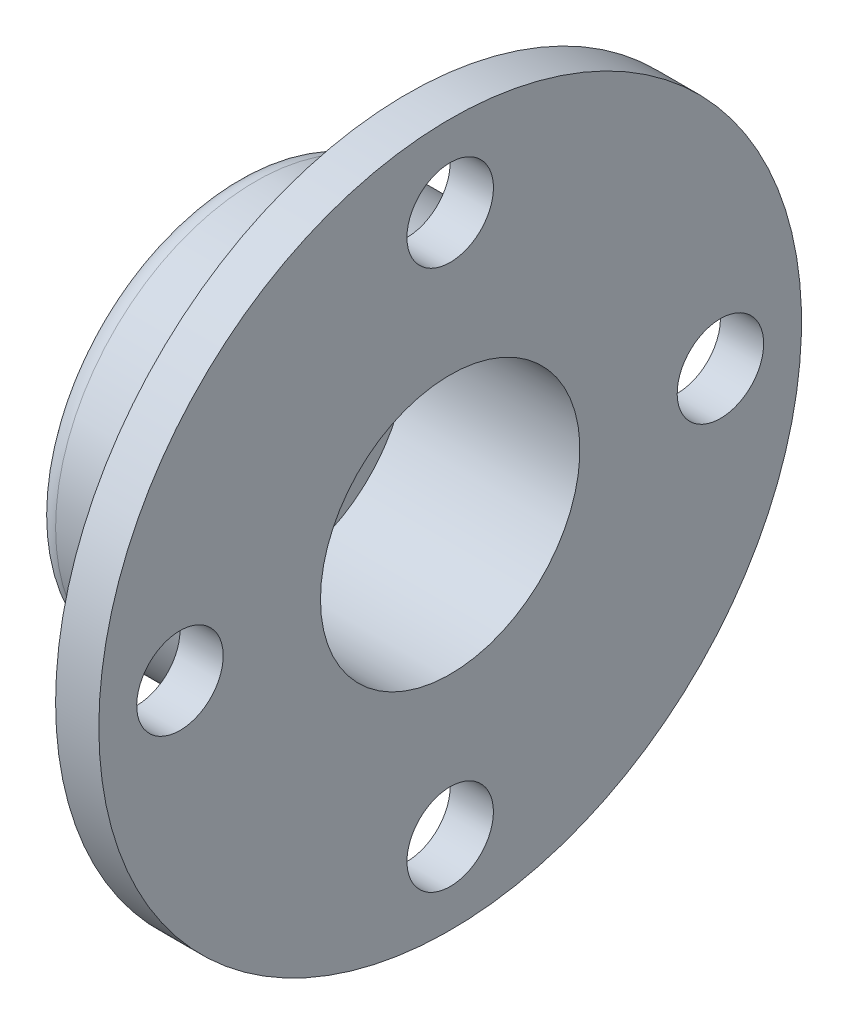
SolidWorks part; units mm, degrees
ref_plane "Front Plane" through (0, 0, 0) normal (0, 0, 1) x (1, 0, 0)
ref_plane "Top Plane" through (0, 0, 0) normal (0, 1, 0) x (1, 0, 0)
ref_plane "Right Plane" through (0, 0, 0) normal (1, 0, 0) x (0, 0, -1)
sketch "Sketch1" plane through (0, 0, 0) normal (0, 1, 0) x (1, 0, 0)
  line L0 (-155.9796, 0) -> (210.4525, 0) construction
  line L1 (0, 50.8) -> (0, 117.5029)
  line L2 (0, 117.5029) -> (101.6, 117.5029)
  line L3 (101.6, 117.5029) -> (101.6, 206.4029)
  line L4 (101.6, 206.4029) -> (127, 206.4029)
  line L5 (0, 50.8) -> (25.4, 50.8)
  line L6 (25.4, 50.8) -> (25.4, 76.2)
  line L7 (25.4, 76.2) -> (127, 76.2)
  line L8 (127, 76.2) -> (127, 206.4029)
  dimension "D1" = 66.7029
  dimension "D2" = 25.4
  dimension "D3" = 25.4
  dimension "D4" = 127
  dimension "D5" = 88.9
  dimension "D6" = 25.4
  dimension "D7" = 50.8
revolve "Revolve6" add sketch "Sketch1" angle 360 about L0
sketch "Sketch5" plane through (101.6, 0, 0) normal (-1, 0, 0) x (0, 0, 1)
  line L0 (0, 0) -> (0, -318.592) construction
  circle A1 centre (0, 158.75) radius 25.4
  circle A2 centre (0, 0) radius 117.5029 construction
  dimension "D1" = 50.8
  dimension "D2" = 158.75
extrude "Cut-Extrude1" cut sketch "Sketch5" against normal through all contours A1
pattern_circular "CirPattern1" count 4 over 360 about axis through (0, 0, 0) along (1, 0, 0) of "Cut-Extrude1"
fillet "Fillet1" radius 12.7 2 edges at (0, 0, 117.5029) (101.6, 0, 117.5029)
